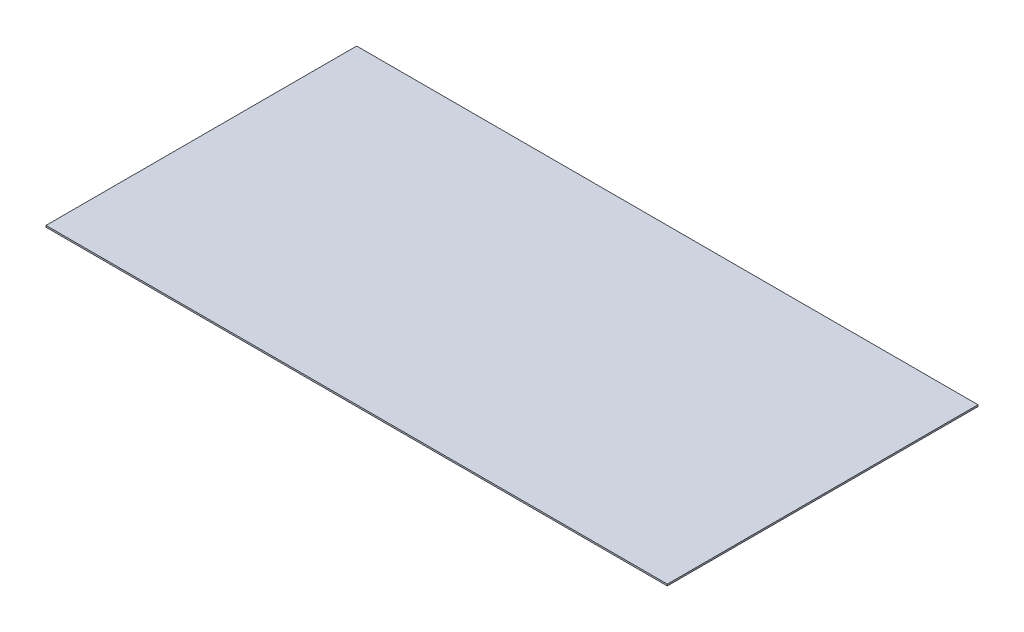
SolidWorks part; units mm, degrees
ref_plane "Front Plane" through (0, 0, 0) normal (0, 0, 1) x (1, 0, 0)
ref_plane "Top Plane" through (0, 0, 0) normal (0, 1, 0) x (1, 0, 0)
ref_plane "Right Plane" through (0, 0, 0) normal (1, 0, 0) x (0, 0, -1)
sketch "Sketch1" plane through (0, 0, 0) normal (0, 1, 0) x (1, 0, 0)
  line L1 (-609.6, -304.8) -> (609.6, -304.8)
  line L2 (-609.6, -304.8) -> (-609.6, 304.8)
  line L3 (-609.6, 304.8) -> (609.6, 304.8)
  line L4 (609.6, -304.8) -> (609.6, 304.8)
  line L5 (-609.6, -304.8) -> (609.6, 304.8) construction
  line L6 (-609.6, 304.8) -> (609.6, -304.8) construction
  point P0 (0, 0)
  dimension "D1" = 609.6
  dimension "D2" = 1219.2
extrude "Boss-Extrude1" add sketch "Sketch1" along normal blind 3.175
